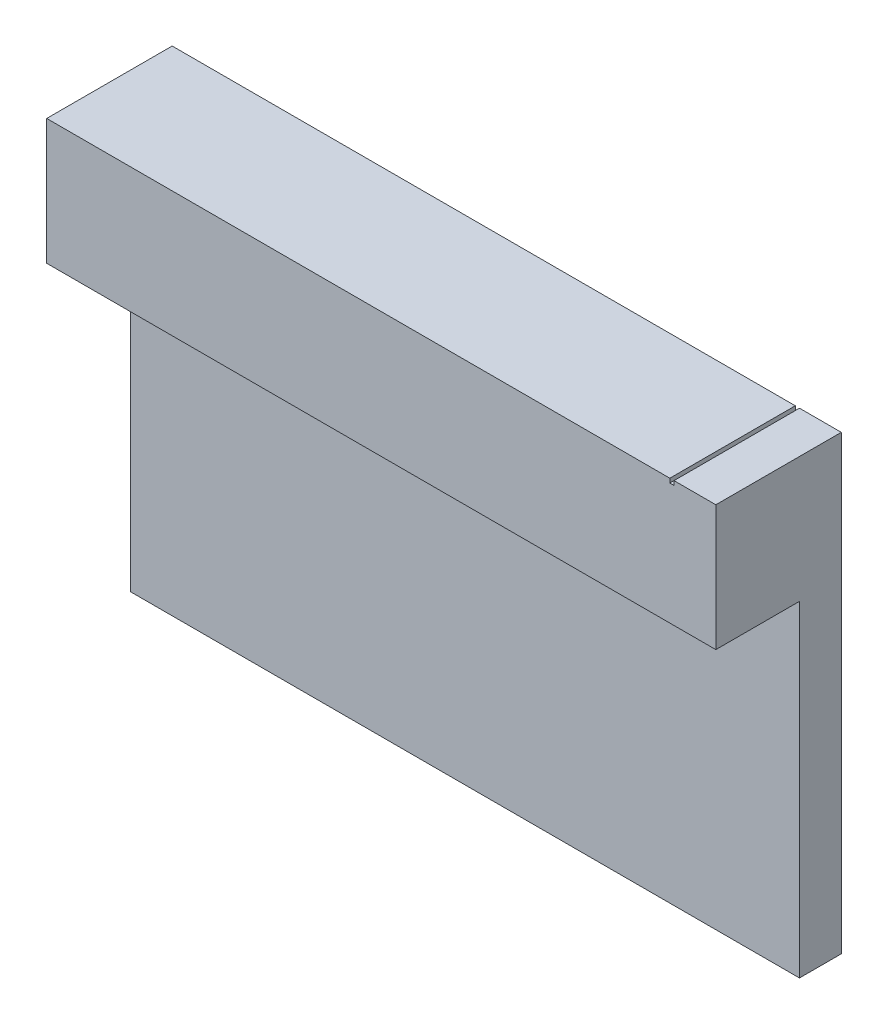
SolidWorks part; units mm, degrees
ref_plane "Plan de face" through (0, 0, 0) normal (0, 0, 1) x (1, 0, 0)
ref_plane "Plan de dessus" through (0, 0, 0) normal (0, 1, 0) x (1, 0, 0)
ref_plane "Plan de droite" through (0, 0, 0) normal (1, 0, 0) x (0, 0, -1)
sketch "Esquisse1" plane through (0, 0, 0) normal (0, 0, 1) x (1, 0, 0)
  line L1 (-52.8124, 21.9483) -> (107.1876, 21.9483)
  line L2 (-52.8124, 21.9483) -> (-52.8124, -86.0517)
  line L3 (-52.8124, -86.0517) -> (107.1876, -86.0517)
  line L4 (107.1876, 21.9483) -> (107.1876, -86.0517)
  dimension "D1" = 160
  dimension "D2" = 108
extrude "Boss.-Extru.1" add sketch "Esquisse1" along normal blind 10
sketch "Esquisse2" plane through (0, 0, 10) normal (0, 0, 1) x (1, 0, 0)
  line L0 (107.1876, -86.0517) -> (107.1876, 21.9483) construction
  line L1 (-52.8124, 21.9483) -> (107.1876, 21.9483)
  line L2 (-52.8124, 21.9483) -> (-52.8124, -8.0517)
  line L3 (-52.8124, -8.0517) -> (107.1876, -8.0517)
  line L4 (107.1876, 21.9483) -> (107.1876, -8.0517)
  dimension "D1" = 30
extrude "Boss.-Extru.2" add sketch "Esquisse2" along normal blind 20
sketch "Esquisse3" plane through (0, 21.9483, 0) normal (0, 1, 0) x (1, 0, 0)
  line L0 (107.1876, 0) -> (-52.8124, 0) construction
  line L1 (96.1876, 0) -> (97.1876, 0)
  line L2 (96.1876, 0) -> (96.1876, -30)
  line L3 (96.1876, -30) -> (97.1876, -30)
  line L4 (97.1876, 0) -> (97.1876, -30)
  line L5 (107.1876, -30) -> (-52.8124, -30) construction
  line L6 (107.1876, -30) -> (107.1876, 0) construction
  dimension "D1" = 10
  dimension "D2" = 1
extrude "Enlèv. mat.-Extru.1" cut sketch "Esquisse3" against normal blind 1
